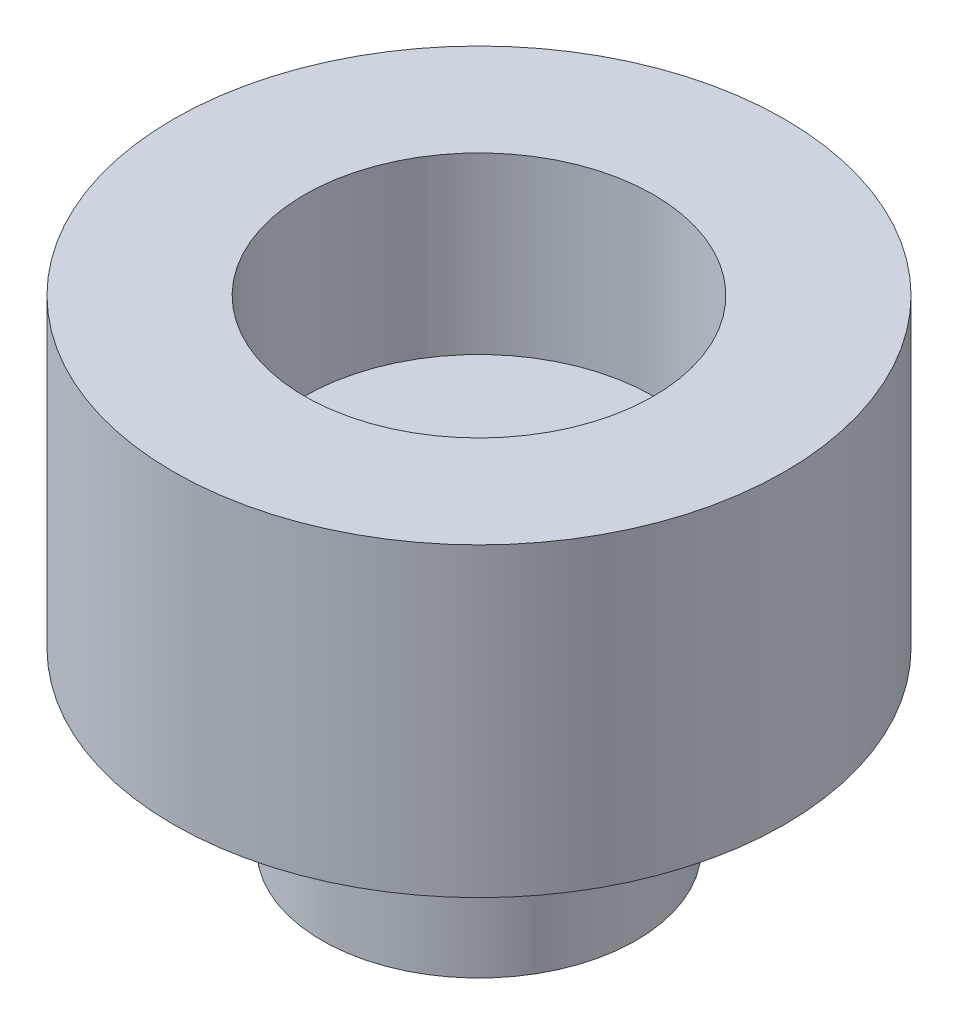
SolidWorks part; units mm, degrees
ref_plane "Plan de face" through (0, 0, 0) normal (0, 0, 1) x (1, 0, 0)
ref_plane "Plan de dessus" through (0, 0, 0) normal (0, 1, 0) x (1, 0, 0)
ref_plane "Plan de droite" through (0, 0, 0) normal (1, 0, 0) x (0, 0, -1)
sketch "Esquisse1" plane through (0, 0, 0) normal (0, 0, 1) x (1, 0, 0)
  line L0 (0, 0) -> (0, 3.5)
  line L1 (0, 3.5) -> (2, 3.5)
  line L2 (2, 3.5) -> (2, 5.5)
  line L3 (2, 5.5) -> (3.5, 5.5)
  line L4 (3.5, 5.5) -> (3.5, 2)
  line L7 (3.5, 2) -> (1.8, 2)
  line L8 (1.8, 2) -> (1.8, 0)
  line L9 (1.8, 0) -> (0, 0)
  dimension "D1" = 1.8
  dimension "D2" = 2
  dimension "D3" = 2
  dimension "D4" = 2
  dimension "D5" = 1.5
  dimension "D6" = 1.5
revolve "Révolution1" add sketch "Esquisse1" angle 360 about L0
